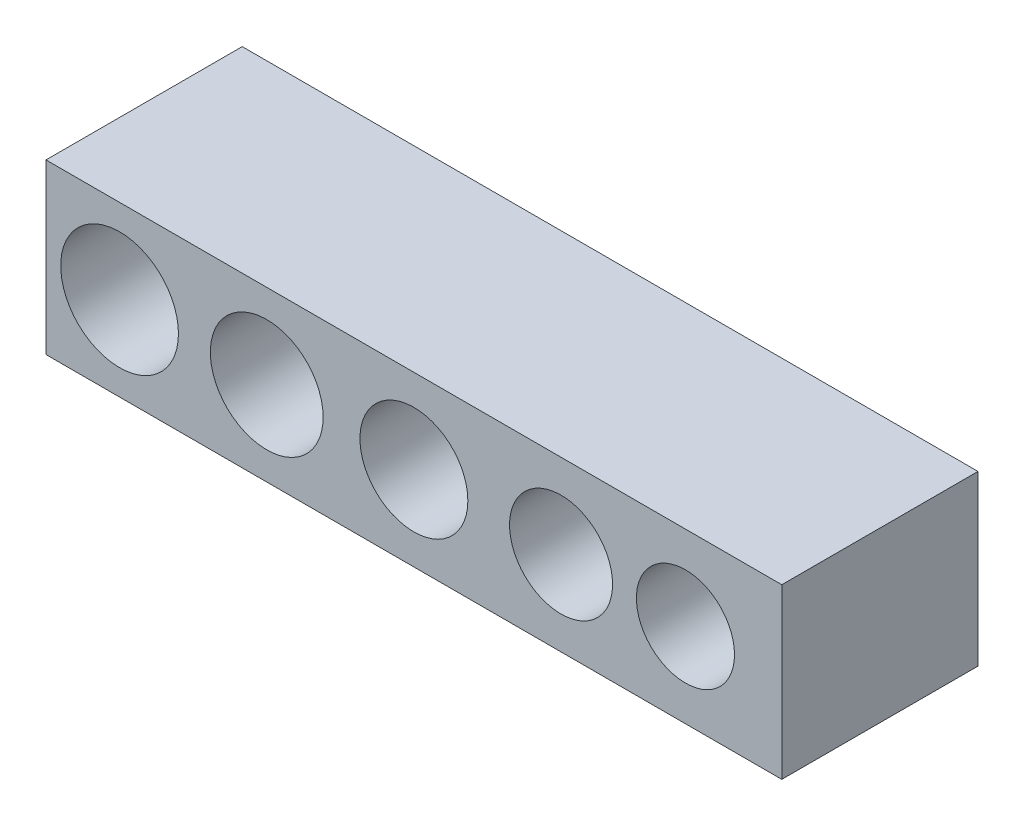
SolidWorks part; units mm, degrees
ref_plane "Front Plane" through (0, 0, 0) normal (0, 0, 1) x (1, 0, 0)
ref_plane "Top Plane" through (0, 0, 0) normal (0, 1, 0) x (1, 0, 0)
ref_plane "Right Plane" through (0, 0, 0) normal (1, 0, 0) x (0, 0, -1)
sketch "Sketch1" plane through (0, 0, 0) normal (0, 0, 1) x (1, 0, 0)
  line L1 (-7.5, -1.7186) -> (7.5, -1.7186)
  line L2 (-7.5, -1.7186) -> (-7.5, 1.7186)
  line L3 (-7.5, 1.7186) -> (7.5, 1.7186)
  line L4 (7.5, -1.7186) -> (7.5, 1.7186)
  line L5 (-7.5, -1.7186) -> (7.5, 1.7186) construction
  line L6 (-7.5, 1.7186) -> (7.5, -1.7186) construction
  circle A0 centre (0, 0) radius 1.1
  circle A1 centre (-3, 0) radius 1.15
  circle A2 centre (3, 0) radius 1.05
  circle A3 centre (5.5361, 0) radius 1
  circle A4 centre (-6, 0) radius 1.2
  dimension "D1" = 2.2
  dimension "D3" = 2.3
  dimension "D4" = 2.1
  dimension "D7" = 2
  dimension "D8" = 2.4
  dimension "D2" = 15
  dimension "D5" = 3
  dimension "D6" = 3
  dimension "D9" = 3
extrude "Boss-Extrude1" add sketch "Sketch1" along normal blind 4 contours L1 L4 L3 L2 A4 A3 A2 A1 A0
